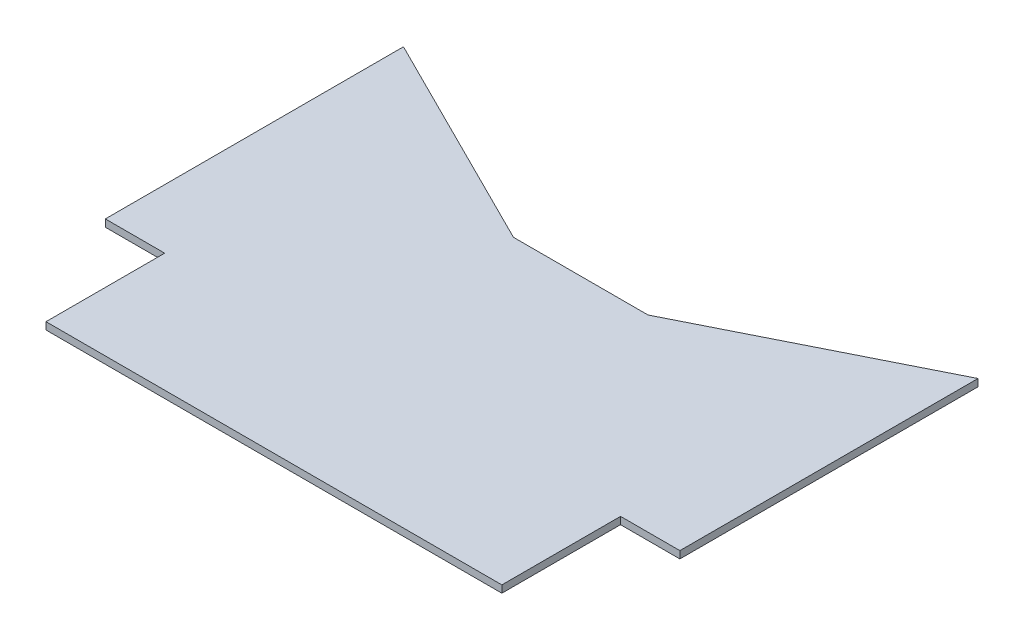
SolidWorks part; units mm, degrees
ref_plane "Front Plane" through (0, 0, 0) normal (0, 0, 1) x (1, 0, 0)
ref_plane "Top Plane" through (0, 0, 0) normal (0, 1, 0) x (1, 0, 0)
ref_plane "Right Plane" through (0, 0, 0) normal (1, 0, 0) x (0, 0, -1)
sketch "Sketch1" plane through (0, 0, 0) normal (0, 1, 0) x (1, 0, 0)
  line L0 (-80.01, 0) -> (80.01, 0)
  line L1 (80.01, 0) -> (80.01, 41.656)
  line L2 (80.01, 41.656) -> (100.838, 41.656)
  line L3 (100.838, 41.656) -> (100.838, 51.308)
  line L4 (100.838, 51.308) -> (23.622, 51.308) construction
  line L5 (23.622, 51.308) -> (23.622, 107.696) construction
  line L7 (0, 0) -> (0, 142.9083) construction
  line L8 (-80.01, 0) -> (-80.01, 41.656)
  line L9 (-23.622, 51.308) -> (-23.622, 107.696) construction
  line L14 (-23.622, 107.696) -> (23.622, 107.696)
  line L15 (100.838, 51.308) -> (100.838, 146.304)
  line L16 (100.838, 146.304) -> (23.622, 107.696)
  line L17 (-100.838, 51.308) -> (-23.622, 51.308) construction
  line L18 (-100.838, 146.304) -> (-23.622, 107.696)
  line L19 (-100.838, 51.308) -> (-100.838, 146.304)
  line L20 (-100.838, 41.656) -> (-100.838, 51.308)
  line L21 (-80.01, 41.656) -> (-100.838, 41.656)
  point P11 (0, 0)
  point P12 (0, 107.696)
  dimension "D1" = 80.01
  dimension "D2" = 41.656
  dimension "D3" = 20.828
  dimension "D4" = 9.652
  dimension "D5" = 77.216
  dimension "D6" = 56.388
  dimension "D7" = 94.996
extrude "Boss-Extrude1" add sketch "Sketch1" along normal blind 2.54
